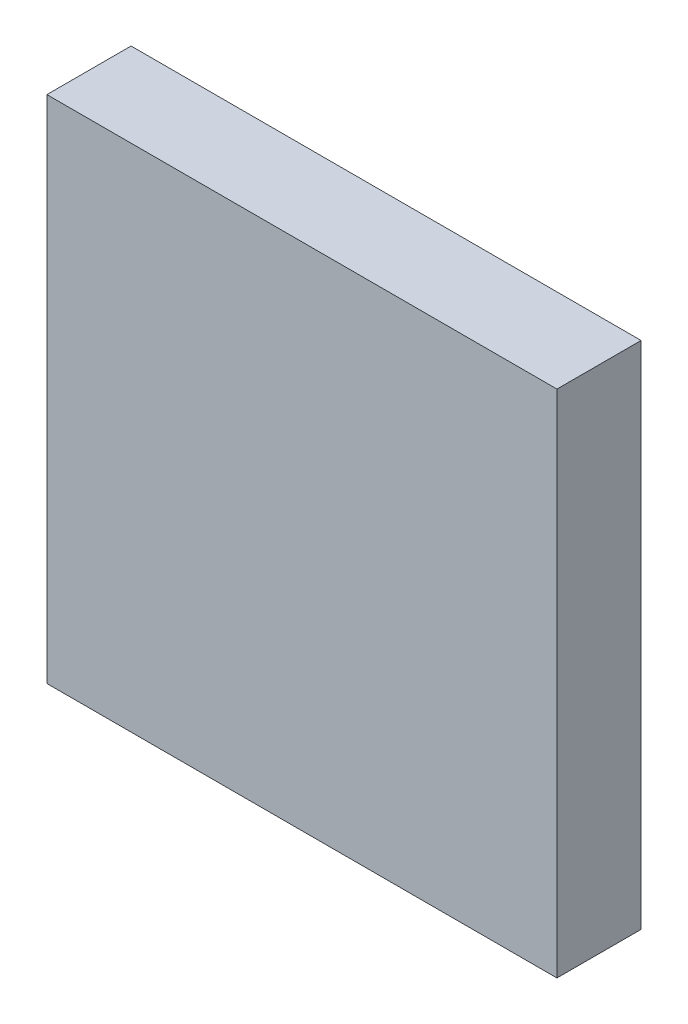
SolidWorks part; units mm, degrees
material "Ceramic Porcelain"
ref_plane "Front Plane" through (0, 0, 0) normal (0, 0, 1) x (1, 0, 0)
ref_plane "Top Plane" through (0, 0, 0) normal (0, 1, 0) x (1, 0, 0)
ref_plane "Right Plane" through (0, 0, 0) normal (1, 0, 0) x (0, 0, -1)
sketch "Sketch2" plane through (0, 0, 0) normal (0, 0, 1) x (1, 0, 0)
  line L1 (-10, 10) -> (10, 10)
  line L2 (-10, 10) -> (-10, -10)
  line L3 (-10, -10) -> (10, -10)
  line L4 (10, 10) -> (10, -10)
  line L5 (-10, 10) -> (10, -10) construction
  line L6 (-10, -10) -> (10, 10) construction
  point P0 (0, 0)
extrude "Boss-Extrude1" add sketch "Sketch2" along normal blind 3.3
